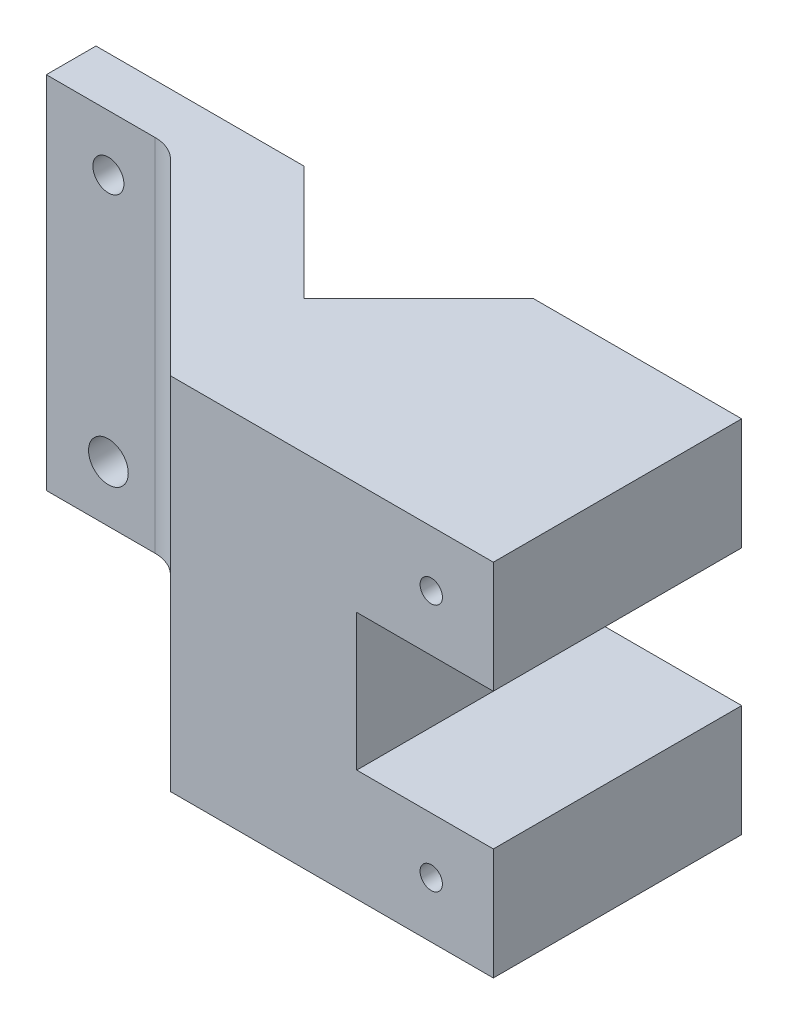
SolidWorks part; units mm, degrees
ref_plane "Front Plane" through (0, 0, 0) normal (0, 0, 1) x (1, 0, 0)
ref_plane "Top Plane" through (0, 0, 0) normal (0, 1, 0) x (1, 0, 0)
ref_plane "Right Plane" through (0, 0, 0) normal (1, 0, 0) x (0, 0, -1)
sketch "Sketch1" plane through (0, 0, 0) normal (0, 1, 0) x (1, 0, 0)
  line L5 (-7.1317, 0) -> (-26, 0)
  line L12 (7.1317, 0) -> (26, 0)
  line L13 (26, 0) -> (26, -20)
  line L14 (26, -20) -> (0, -20)
  line L17 (-26, 0) -> (-26, -4)
  line L19 (-16, -4) -> (0, -20)
  line L20 (-7.1317, 0) -> (0, -7.1317)
  line L21 (0, -7.1317) -> (7.1317, 0)
  line L22 (-26, -4) -> (-16, -4)
  circle A2 centre (0, 1.6718) radius 6.225 construction
  circle A3 centre (0, 1) radius 5.75 construction
  point P0 (0, 0)
  dimension "D5" = 26
  dimension "D9" = 12.45
  dimension "D10" = 11.5
  dimension "D2" = 10
  dimension "D3" = 1
  dimension "D4" = 1.6718
  dimension "D6" = 20
  dimension "D8" = 4
extrude "Boss-Extrude1" add sketch "Sketch1" along normal mid plane 29
sketch "Sketch4" plane through (0, 0, 20) normal (0, 0, 1) x (1, 0, 0)
  line L0 (26, 5.5) -> (15, 5.5)
  line L1 (26, 14.5) -> (26, -14.5) construction
  line L2 (15, 5.5) -> (15, -5.5)
  line L3 (15, -5.5) -> (26, -5.5)
  line L4 (0, 0) -> (26, 0) construction
  line L5 (15.3432, 0) -> (-15.3432, 0) construction
  line L7 (26, 5.5) -> (26, -5.5)
  circle A0 centre (21, 10) radius 0.9
  circle A1 centre (21, -10) radius 0.9
  point P13 (15, 0)
  dimension "D1" = 1.8
  dimension "D2" = 11
  dimension "D4" = 20
  dimension "D5" = 10
  dimension "D7" = 11
  dimension "D8" = 5
extrude "Cut-Extrude2" cut sketch "Sketch4" against normal through all and the other way through all
sketch "Sketch5" plane through (0, 0, 4) normal (0, 0, 1) x (1, 0, 0)
  line L4 (-26, 0) -> (0, 0) construction
  line L5 (-26, 14.5) -> (-26, -14.5) construction
  circle A0 centre (-21, 10) radius 1.25
  circle A1 centre (-21, -10) radius 1.6
  dimension "D1" = 2.5
  dimension "D2" = 3.2
  dimension "D3" = 5
  dimension "D4" = 20
  dimension "D5" = 10
extrude "Cut-Extrude3" cut sketch "Sketch5" against normal through all
fillet "Fillet1" radius 3 1 edges at (-16, 0, 4)
sketch "Sketch8" plane through (0, 0, 0) normal (0, 1, 0) x (1, 0, 0)
  line L1 (-7.1317, 0) -> (-26, 0) construction
  line L3 (9.253, 0) -> (-9.253, 0)
  line L8 (0, -9.253) -> (8.1924, -1.0607)
  line L9 (-8.1924, -1.0607) -> (0, -9.253)
  line L10 (0, -9.253) -> (9.253, 0)
  line L11 (-9.253, 0) -> (0, -9.253)
  point P0 (-10.9901, 3.2229)
  point P4 (-4.5473, 0)
  point P6 (4.4233, 0)
  dimension "D1" = 1.5
extrude "Cut-Extrude5" cut sketch "Sketch8" against normal through all both and the other way through all
sketch "Sketch9" plane through (0, 0, 0) normal (0, 1, 0) x (1, 0, 0)
  line L2 (0, -9.253) -> (9.253, 0) construction
  line L3 (-9.253, 0) -> (0, -9.253) construction
  line L4 (-7.1317, 2.1213) -> (0, -5.0104)
  line L5 (0, -5.0104) -> (7.1317, 2.1213)
  line L6 (-5.0104, 0) -> (0, -5.0104)
  line L7 (0, -5.0104) -> (5.0104, 0)
  line L8 (0, -9.253) -> (9.253, 0)
  line L9 (-9.253, 0) -> (0, -9.253)
  line L10 (-7.1317, 0) -> (-26, 0) construction
  line L11 (9.253, 0) -> (5.0104, 0)
  line L13 (-5.0104, 0) -> (-9.253, 0)
  point P6 (13.1013, 0)
  dimension "D1" = 3
extrude "Boss-Extrude2" [suppressed] add sketch "Sketch9" along normal blind 15 separate body
